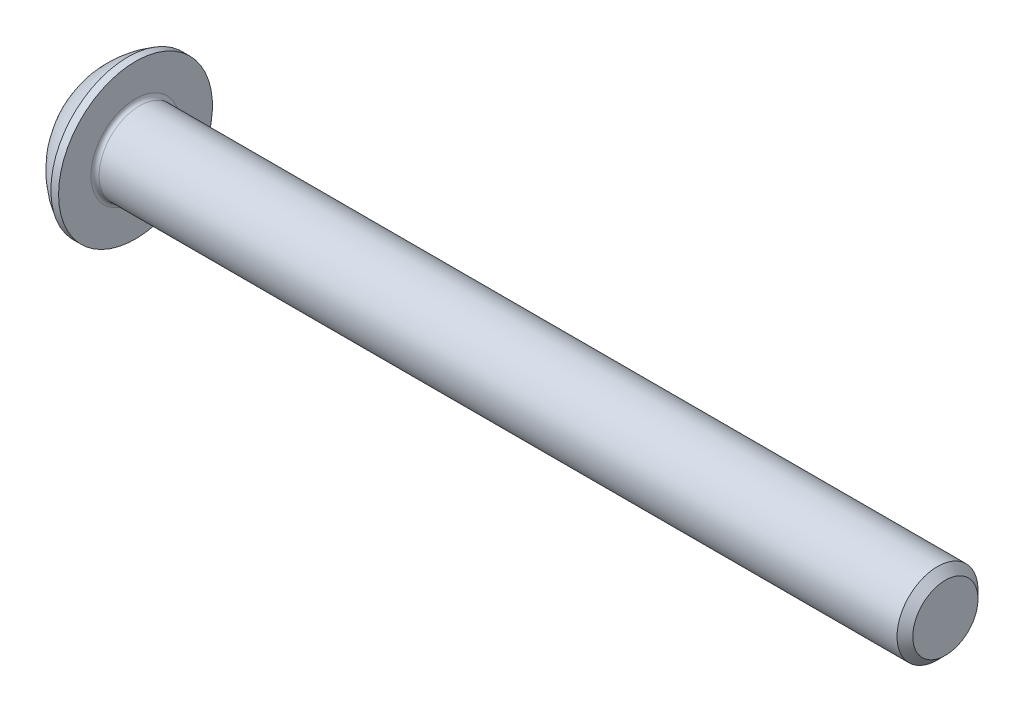
SolidWorks part; units mm, degrees
ref_plane "Plane1" through (0, 0, 0) normal (0, 0, 1) x (1, 0, 0)
ref_plane "Plane2" through (0, 0, 0) normal (0, 1, 0) x (1, 0, 0)
ref_plane "Plane3" through (0, 0, 0) normal (1, 0, 0) x (0, 0, -1)
sketch "BodySke" plane through (0, 0, 0) normal (0, 0, 1) x (1, 0, 0)
  line L0 (42.2, 0) -> (42.2, 1.61)
  line L1 (41.81, 2) -> (2.2, 2)
  line L2 (2.2, 2) -> (2.2, 3.8)
  line L3 (2.2, 3.8) -> (1.82, 3.8)
  line L4 (0, 0) -> (101.6, 0) construction
  line L5 (2.2, -3.8) -> (1.82, -3.8) construction
  line L6 (55.6768, -2) -> (2.2, -2) construction
  line L7 (42.2, 0) -> (0, 0)
  line L8 (0, 1.9) -> (0, -1.9) construction
  line L9 (0, 0) -> (0, 1.9)
  line L10 (42.2, 1.61) -> (41.81, 2)
  line L11 (42.2, -1.61) -> (41.81, -2) construction
  line L12 (2.9, 9.525) -> (2.9, -2) construction
  line L13 (22.2, 9.525) -> (22.2, -2) construction
  arc A1 (0, 1.9) -> (1.82, 3.8) centre (3.8853, 0) cw
  dimension "Diameter" = 4
  dimension "Length" = 40
  dimension "Head_dia" = 7.6
  dimension "D1" = 3.8
  dimension "Head_ht" = 2.2
  dimension "Head_side_ht" = 0.38
  dimension "Minor_dia" = 3.22
  dimension "Body_ch_ang" = 45
  dimension "Advance" = 0.7
  dimension "Thread_nom" = 20
revolve "BaseBody" add sketch "BodySke" angle 360 about L4
cosmetic thread "ThreadCosmetic" [suppressed] parameters "Thread_length"=20, "Thread_minor"=3.22
fillet "Fillet1" radius 0.2 1 edges at (2.2, 0, 2)
sketch "Sketch2" plane through (0, 0, 0) normal (0, 0, 1) x (1, 0, 0)
  line L0 (0, 1.25) -> (1.3, 1.25)
  line L1 (1.3, 1.25) -> (2.0217, 0)
  line L3 (2.0217, 0) -> (0, 0)
  line L4 (0, 0) -> (0, 1.25)
  line L5 (0, -1.25) -> (1.3, -1.25) construction
  line L6 (0, 0) -> (47.625, 0) construction
  dimension "D2" = 60
  dimension "PreBroach_depth" = 1.3
  dimension "PreBroach_dia" = 2.5
revolve "PreBroach" cut sketch "Sketch2" angle 360 about L6
sketch "Sketch3" plane through (0, 0, 0) normal (1, 0, 0) x (0, 0, -1)
  line L0 (-1.25, -0.7217) -> (-1.25, 0.7217)
  line L1 (-1.25, 0.7217) -> (0, 1.4434)
  line L2 (0, 1.4434) -> (1.25, 0.7217)
  line L3 (1.25, 0.7217) -> (1.25, -0.7217)
  line L4 (1.25, -0.7217) -> (0, -1.4434)
  line L5 (0, -1.4434) -> (-1.25, -0.7217)
  dimension "Hex_size" = 2.5
  dimension "D3" = 2.5
  dimension "D1" = 1.25
  dimension "D2" = 1.25
extrude "Hex" cut sketch "Sketch3" along normal blind 1.3
sketch "ThdSchSke" plane through (0, 0, 0) normal (0, 0, 1) x (1, 0, 0)
  line L0 (22.2, -1.61) -> (21.9269, -2)
  line L1 (22.2, -1.61) -> (22.4731, -2)
  line L2 (22.4731, -2) -> (22.4731, -2.5)
  line L3 (-3.175, 0) -> (5.1513, 0) construction
  line L5 (22.4731, -2.5) -> (21.9269, -2.5)
  line L6 (21.9269, -2.5) -> (21.9269, -2)
  dimension "Diameter" = 4
  dimension "Thread_minor" = 3.22
  dimension "SideAngle" = 55
  dimension "VeeAngle" = 70
  dimension "Overcut" = 5
  dimension "Start" = 22.2
revolve "ThreadSchematic" [suppressed] cut sketch "ThdSchSke" angle 360 about L3
pattern_linear "ThdSchPat" [suppressed]
equation "\"D1@BodySke\" = \"Head_dia@BodySke\" * .5"
equation "\"Thread_minor@ThreadCosmetic\" = \"Minor_dia@BodySke\""
equation "\"D1@Sketch3\" = \"Hex_size@Sketch3\" / 2"
equation "\"D2@Sketch3\" = \"D1@Sketch3\""
equation "\"D3@Sketch3\" = \"Hex_size@Sketch3\""
equation "\"Thread_length@ThreadCosmetic\" = ((sgn( (\"Length@BodySke\" - \"Advance@BodySke\" * 2.0) - \"Thread_nom@BodySke\" )-1)*( (\"Length@BodySke\" - \"Advance@BodySke\" * 2.0) - \"Thread_nom@BodySke\" ))/-2+ \"Thread_nom@BodySke\""
equation "\"Thread_minor@ThdSchSke\" = \"Minor_dia@BodySke\""
equation "\"Diameter@ThdSchSke\" = \"Diameter@BodySke\""
equation "\"Overcut@ThdSchSke\" = \"Diameter@BodySke\" * 1.25"
equation "\"Start@ThdSchSke\" = \"Head_ht@BodySke\" + \"Length@BodySke\" - \"Thread_length@ThreadCosmetic\"  '---Non-countersunk---"
equation "\"Num_threads@ThdSchPat\" = int( \"Thread_length@ThreadCosmetic\" / \"Advance@BodySke\" + 0.999 )  + 1"
equation "\"Advance@ThdSchPat\" = \"Thread_length@ThreadCosmetic\" /  (\"Num_threads@ThdSchPat\" - 1) 'relax it"
equation "\"Num_threads@ThdSchPat\" = \"Num_threads@ThdSchPat\" - sgn( \"Num_threads@ThdSchPat\" - 1) '---chamfered tips only---"
